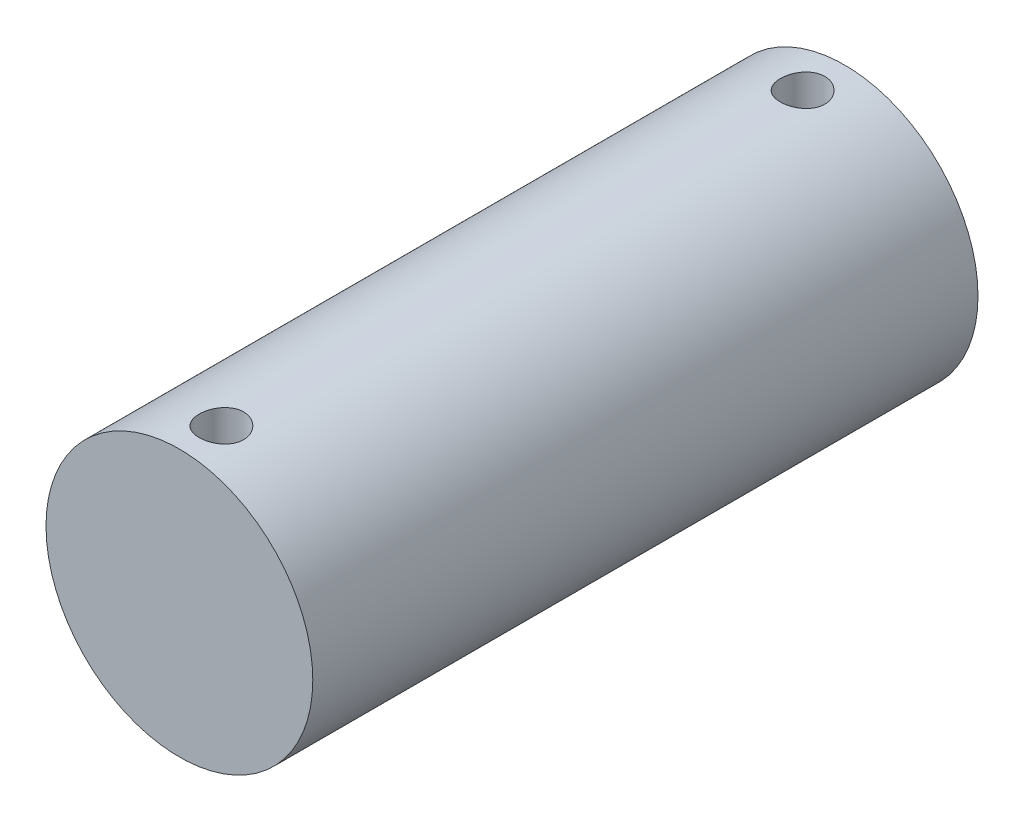
SolidWorks part; units mm, degrees
ref_plane "Alzado" through (0, 0, 0) normal (0, 0, 1) x (1, 0, 0)
ref_plane "Planta" through (0, 0, 0) normal (0, 1, 0) x (1, 0, 0)
ref_plane "Vista lateral" through (0, 0, 0) normal (1, 0, 0) x (0, 0, -1)
sketch "Croquis1" plane through (0, 0, 0) normal (0, 0, 1) x (1, 0, 0)
  circle A0 centre (0, 0) radius 19.05
  dimension "D1" = 38.1
extrude "Saliente-Extruir1" add sketch "Croquis1" along normal blind 95
sketch "Croquis2" plane through (0, 0, 0) normal (0, 1, 0) x (1, 0, 0)
  line L0 (0, 0) -> (0, -6) construction
  line L1 (-19.05, -47.5) -> (19.05, -47.5) construction
  line L2 (-19.05, 0) -> (-19.05, -95) construction
  line L3 (19.05, -95) -> (19.05, 0) construction
  line L4 (0, -95) -> (0, -89) construction
  circle A0 centre (0, -6) radius 3.175
  circle A1 centre (0, -89) radius 3.175
  dimension "D1" = 6.35
  dimension "D2" = 6
extrude "Cortar-Extruir1" cut sketch "Croquis2" against normal mid plane 70
